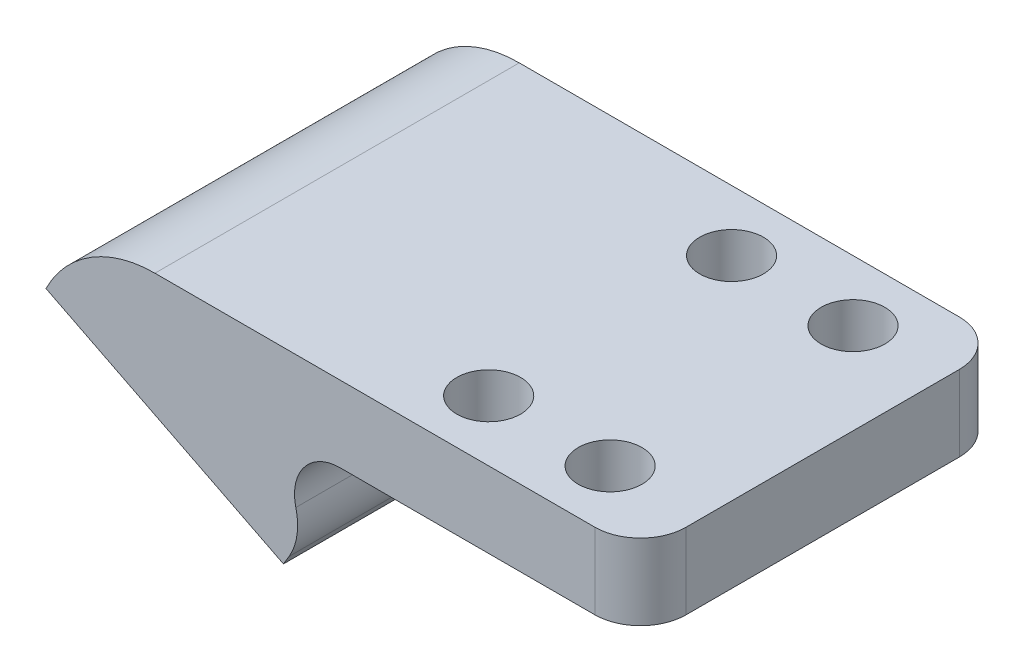
SolidWorks part; units mm, degrees
ref_plane "Plan de face" through (0, 0, 0) normal (0, 0, 1) x (1, 0, 0)
ref_plane "Plan de dessus" through (0, 0, 0) normal (0, 1, 0) x (1, 0, 0)
ref_plane "Plan de droite" through (0, 0, 0) normal (1, 0, 0) x (0, 0, -1)
sketch "Esquisse1" plane through (0, 0, 0) normal (0, 0, 1) x (1, 0, 0)
  line L1 (-6.5596, 0) -> (10.4404, 0)
  line L2 (-6.5596, 0) -> (-6.5596, 5)
  line L3 (-6.5596, 5) -> (10.4404, 5)
  line L4 (10.4404, 0) -> (10.4404, 5)
  dimension "D1" = 5
  dimension "D2" = 17
extrude "Boss.-Extru.1" add sketch "Esquisse1" along normal blind 24
sketch "Esquisse2" plane through (0, 0, 24) normal (0, 0, 1) x (1, 0, 0)
  line L0 (-6.5596, 5) -> (-16.4711, 5)
  line L1 (-16.4711, 5) -> (-0.5016, -3.0561)
  line L2 (-16.4711, 5) -> (-18.7231, 0.5359)
  line L3 (-18.7231, 0.5359) -> (-3.0805, -7.3553)
  line L4 (-3.0805, -7.3553) -> (-0.5016, -3.0561)
  line L5 (-6.5596, 5) -> (-6.5596, 0) construction
  line M4 (-6.5596, 5) -> (-6.5596, 0)
extrude "Boss.-Extru.2" add sketch "Esquisse2" against normal blind 24 contours L3 L4 L1 L2 | L0 L1 M4
fillet "Congé1" radius 4 1 edges at (-0.5016, -3.0561, 12)
fillet "Congé2" radius 8 1 edges at (-16.4711, 5, 12)
fillet "Congé3" radius 3 1 edges at (-6.5596, 0, 12)
sketch "Esquisse3" plane through (10.4404, 0, 0) normal (1, 0, 0) x (0, 0, -1)
  line L1 (0, 0) -> (-24, 0)
  line L2 (0, 0) -> (0, 5)
  line L3 (0, 5) -> (-24, 5)
  line L4 (-24, 0) -> (-24, 5)
extrude "Boss.-Extru.3" add sketch "Esquisse3" along normal blind 10
sketch "Esquisse4" plane through (0, 5, 0) normal (0, 1, 0) x (1, 0, 0)
  line L0 (14.4404, -4) -> (6.4404, -4) construction
  line L2 (6.4404, -4) -> (6.4404, -20) construction
  line L3 (6.4404, -12) -> (20.4404, -12) construction
  line L4 (20.4404, 0) -> (20.4404, -24) construction
  circle A0 centre (6.4404, -4) radius 2.1
  circle A1 centre (14.4404, -4) radius 2.1
  circle A2 centre (6.4404, -20) radius 2.1
  circle A3 centre (14.4404, -20) radius 2.1
  circle A4 centre (6.4404, -20) radius 2.1
  dimension "D4" = 4.2
  dimension "D1" = 8
  dimension "D2" = 16
  dimension "D3" = 6
extrude "Enlèv. mat.-Extru.1" cut sketch "Esquisse4" against normal blind 10 contours A2 | A3 | A1 | A0
fillet "Congé4" radius 3 2 edges at (20.4404, 2.5, 0) (20.4404, 2.5, 24)
sketch "Esquisse5" plane through (-3.5827, -7.102, 0) normal (-0.4504, -0.8928, 0) x (0.8928, -0.4504, 0)
  line L0 (-16.9578, 12) -> (0.5625, 12) construction
  line L1 (-16.9578, 0) -> (-16.9578, 24) construction
  line L2 (0.5625, 0) -> (0.5625, 24) construction
  line L3 (-8.1977, 17) -> (-8.1977, 7) construction
  line L4 (-16.9578, 0) -> (0.5625, 0) construction
  line L5 (-8.1977, 0) -> (-8.1977, 24) construction
  line L6 (-16.9578, 24) -> (0.5625, 24) construction
  line L7 (-5.6977, 17) -> (-5.6977, 7)
  line L8 (-10.6977, 17) -> (-10.6977, 7)
  arc A0 (-5.6977, 17) -> (-10.6977, 17) centre (-8.1977, 17) ccw
  arc A1 (-10.6977, 7) -> (-5.6977, 7) centre (-8.1977, 7) ccw
  point P14 (-8.1977, 12)
  dimension "D1" = 10
  dimension "D2" = 5
extrude "Boss.-Extru.4" add sketch "Esquisse5" along normal blind 5
